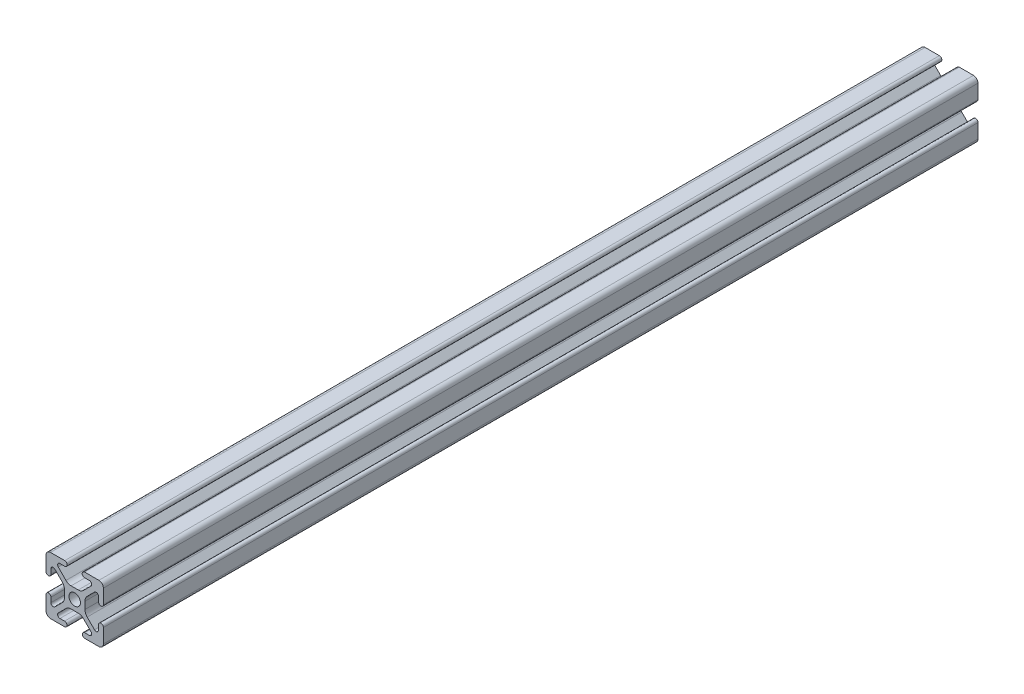
SolidWorks part; units mm, degrees
ref_plane "Front" through (0, 0, 0) normal (0, 0, 1) x (1, 0, 0)
ref_plane "Top" through (0, 0, 0) normal (0, 1, 0) x (1, 0, 0)
ref_plane "Right" through (0, 0, 0) normal (1, 0, 0) x (0, 0, -1)
ref_plane "Plane1" through (0, 0, -381) normal (0, 0, -1) x (-1, 0, 0)
sketch "Sketch1" plane through (0, 0, -381) normal (0, 0, -1) x (-1, 0, 0)
  line L0 (12.5, 4.32) -> (12.5, 10.5371)
  line L1 (10.5371, 12.5) -> (4.32, 12.5)
  line L2 (4.32, 10.36) -> (6.42, 10.36)
  line L3 (7.1337, 8.6353) -> (3.7953, 5.3018)
  line L4 (1.5554, 4.375) -> (-1.5554, 4.375)
  line L5 (-3.7953, 5.3018) -> (-7.1337, 8.6353)
  line L6 (-6.42, 10.36) -> (-4.32, 10.36)
  line L7 (-4.32, 12.5) -> (-10.5371, 12.5)
  line L8 (-12.5, 10.5371) -> (-12.5, 4.32)
  line L9 (-10.36, 4.32) -> (-10.36, 6.3969)
  line L10 (-8.6363, 7.1116) -> (-5.4322, 3.9121)
  line L11 (-4.455, 1.5554) -> (-4.455, -1.5554)
  line L12 (-5.4322, -3.9121) -> (-8.6363, -7.1116)
  line L13 (-10.36, -6.3969) -> (-10.36, -4.32)
  line L14 (-12.5, -4.32) -> (-12.5, -10.5371)
  line L15 (-10.5371, -12.5) -> (-4.3879, -12.5)
  line L16 (-4.3879, -10.36) -> (-6.42, -10.36)
  line L17 (-7.1337, -8.6353) -> (-3.7953, -5.3018)
  line L18 (-1.5554, -4.375) -> (1.5554, -4.375)
  line L19 (3.7953, -5.3018) -> (7.1337, -8.6353)
  line L20 (6.42, -10.36) -> (4.3879, -10.36)
  line L21 (4.3879, -12.5) -> (10.5371, -12.5)
  line L22 (12.5, -10.5371) -> (12.5, -4.32)
  line L23 (10.36, -4.32) -> (10.36, -6.3969)
  line L24 (8.6363, -7.1116) -> (5.4322, -3.9121)
  line L25 (4.455, -1.5554) -> (4.455, 1.5554)
  line L26 (5.4322, 3.9121) -> (8.6363, 7.1116)
  line L27 (10.36, 6.3969) -> (10.36, 4.32)
  circle A0 centre (0, 0) radius 2.5
  arc A1 (12.5, 10.5371) -> (10.5371, 12.5) centre (10.5371, 10.5371) ccw
  arc A2 (4.32, 12.5) -> (4.32, 10.36) centre (4.32, 11.43) ccw
  arc A3 (6.42, 10.36) -> (7.1337, 8.6353) centre (6.42, 9.35) cw
  arc A4 (3.7953, 5.3018) -> (1.5554, 4.375) centre (1.5554, 7.545) cw
  arc A5 (-1.5554, 4.375) -> (-3.7953, 5.3018) centre (-1.5554, 7.545) cw
  arc A6 (-7.1337, 8.6353) -> (-6.42, 10.36) centre (-6.42, 9.35) cw
  arc A7 (-4.32, 10.36) -> (-4.32, 12.5) centre (-4.32, 11.43) ccw
  arc A8 (-10.5371, 12.5) -> (-12.5, 10.5371) centre (-10.5371, 10.5371) ccw
  arc A9 (-12.5, 4.32) -> (-10.36, 4.32) centre (-11.43, 4.32) ccw
  arc A10 (-10.36, 6.3969) -> (-8.6363, 7.1116) centre (-9.35, 6.3969) cw
  arc A11 (-5.4322, 3.9121) -> (-4.455, 1.5554) centre (-7.7855, 1.5554) cw
  arc A12 (-4.455, -1.5554) -> (-5.4322, -3.9121) centre (-7.7855, -1.5554) cw
  arc A13 (-8.6363, -7.1116) -> (-10.36, -6.3969) centre (-9.35, -6.3969) cw
  arc A14 (-10.36, -4.32) -> (-12.5, -4.32) centre (-11.43, -4.32) ccw
  arc A15 (-12.5, -10.5371) -> (-10.5371, -12.5) centre (-10.5371, -10.5371) ccw
  arc A16 (-4.3879, -12.5) -> (-4.3879, -10.36) centre (-4.3879, -11.43) ccw
  arc A17 (-6.42, -10.36) -> (-7.1337, -8.6353) centre (-6.42, -9.35) cw
  arc A18 (-3.7953, -5.3018) -> (-1.5554, -4.375) centre (-1.5554, -7.545) cw
  arc A19 (1.5554, -4.375) -> (3.7953, -5.3018) centre (1.5554, -7.545) cw
  arc A20 (7.1337, -8.6353) -> (6.42, -10.36) centre (6.42, -9.35) cw
  arc A21 (4.3879, -10.36) -> (4.3879, -12.5) centre (4.3879, -11.43) ccw
  arc A22 (10.5371, -12.5) -> (12.5, -10.5371) centre (10.5371, -10.5371) ccw
  arc A23 (12.5, -4.32) -> (10.36, -4.32) centre (11.43, -4.32) ccw
  arc A24 (10.36, -6.3969) -> (8.6363, -7.1116) centre (9.35, -6.3969) cw
  arc A25 (5.4322, -3.9121) -> (4.455, -1.5554) centre (7.7855, -1.5554) cw
  arc A26 (4.455, 1.5554) -> (5.4322, 3.9121) centre (7.7855, 1.5554) cw
  arc A27 (8.6363, 7.1116) -> (10.36, 6.3969) centre (9.35, 6.3969) cw
  arc A28 (10.36, 4.32) -> (12.5, 4.32) centre (11.43, 4.32) ccw
  dimension "D1" = 5
  dimension "D2" = 1.9629
  dimension "D3" = 1.07
  dimension "D4" = 1.01
  dimension "D5" = 3.17
  dimension "D6" = 3.3305
  dimension "D7" = 1.5554
  dimension "D8" = 3.7953
  dimension "D9" = 4.32
  dimension "D10" = 4.3879
  dimension "D11" = 4.455
  dimension "D12" = 1.5554
  dimension "D13" = 11.43
  dimension "D14" = 11.43
extrude "Boss-Extrude1" add sketch "Sketch1" against normal blind 381
